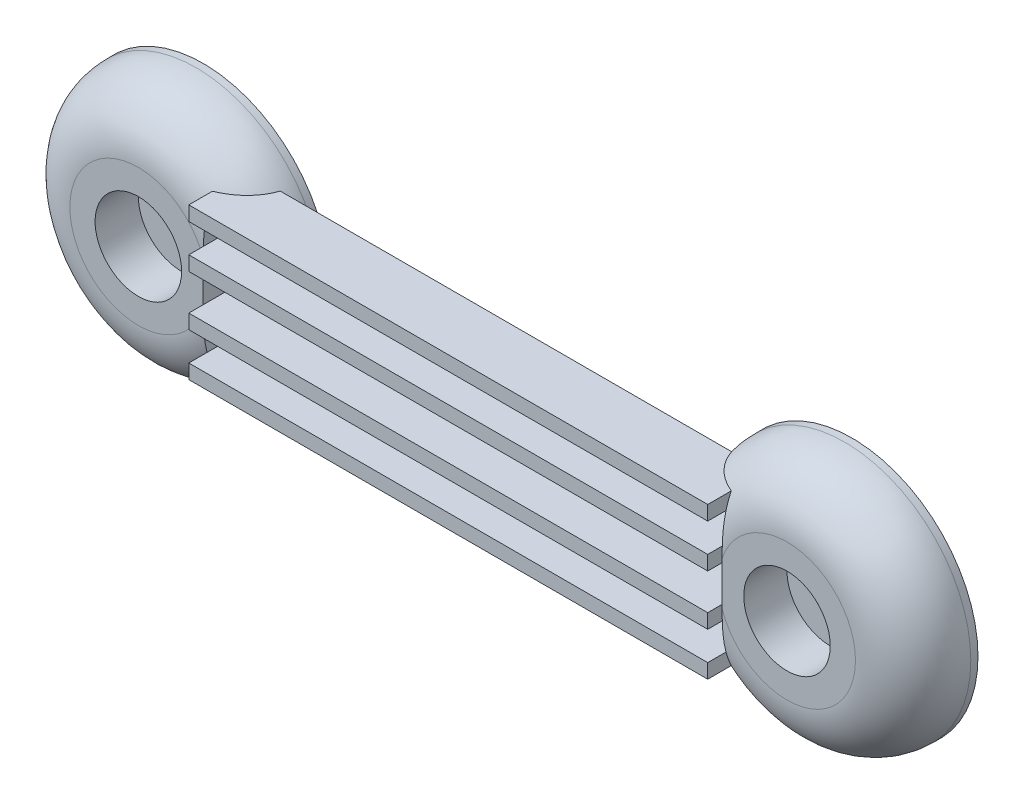
SolidWorks part; units mm, degrees
ref_plane "Alzado" through (0, 0, 0) normal (0, 0, 1) x (1, 0, 0)
ref_plane "Planta" through (0, 0, 0) normal (0, 1, 0) x (1, 0, 0)
ref_plane "Vista lateral" through (0, 0, 0) normal (1, 0, 0) x (0, 0, -1)
sketch "Croquis1" plane through (0, 0, 0) normal (0, 0, 1) x (1, 0, 0)
  line L0 (-45, 0) -> (45, 0) construction
  circle A0 centre (45, 0) radius 17.5
  circle A1 centre (-45, 0) radius 17.5
  dimension "D1" = 90
extrude "Saliente-Extruir1" add sketch "Croquis1" along normal blind 9
fillet "Redondeo1" radius 8 1 edges at (-27.5, 0, 9)
fillet "Redondeo2" radius 8 1 edges at (62.5, 0, 9)
ref_plane "Plano1" through (0, 0, 3) normal (0, 0, 1) x (1, 0, 0)
sketch "Croquis5" plane through (0, 0, 3) normal (0, 0, 1) x (1, 0, 0)
  line L0 (-36, -10.5) -> (36, -10.5)
  line L1 (-36, -10.5) -> (-36, 10.5)
  line L2 (36, -10.5) -> (36, 10.5)
  line L3 (-36, 10.5) -> (36, 10.5)
  line L4 (-36, -10.5) -> (36, 10.5) construction
  line L5 (36, -10.5) -> (-36, 10.5) construction
  circle A0 centre (45, 0) radius 9.5 construction
  point P1 (0, 0)
  dimension "D1" = 10.5
  dimension "D2" = 9
extrude "Saliente-Extruir2" add sketch "Croquis5" along normal blind 8
sketch "Croquis6" plane through (0, 0, 11) normal (0, 0, 1) x (1, 0, 0)
  line L4 (-36, 10.5) -> (-36, -10.5)
  line L5 (-36, -10.5) -> (36, -10.5)
  line L6 (36, -10.5) -> (36, 10.5)
  line L7 (36, 10.5) -> (-36, 10.5)
  line L8 (-36, 10.5) -> (-36, -10.5)
  line L9 (-36, -10.5) -> (36, -10.5)
  line L10 (36, -10.5) -> (36, 10.5)
  line L11 (36, 10.5) -> (-36, 10.5)
  line L12 (36, 8.5) -> (-36, 8.5)
  line L13 (-36, -8.5) -> (36, -8.5)
  line L14 (-36, -4.5) -> (36, -4.5)
  line L19 (36, 4.5) -> (-36, 4.5)
  line L20 (36, 2.5) -> (-36, 2.5)
  line L21 (-36, -2.5) -> (36, -2.5)
  line M5 (-36, 10.5) -> (-36, -10.5)
  dimension "D1" = 0
  dimension "D2" = 2
  dimension "D3" = 2
  dimension "D4" = 4
  dimension "D5" = 4
  dimension "D6" = 2
  dimension "D7" = 2
extrude "Cortar-Extruir1" cut sketch "Croquis6" against normal blind 7 contours L19 L10 L12 L8 | L8 L21 L10 L20 | L14 L13 L10 M5
sketch "Croquis8" plane through (0, 0, 9) normal (0, 0, 1) x (1, 0, 0)
  circle A0 centre (-45, 0) radius 6
  circle A1 centre (45, 0) radius 6
extrude "Cortar-Extruir2" cut sketch "Croquis8" against normal blind 6
sketch "Croquis9" plane through (0, 0, 3) normal (0, 0, 1) x (1, 0, 0)
  circle A0 centre (45, 0) radius 2.5
  circle A1 centre (-45, 0) radius 2.5
extrude "Cortar-Extruir3" cut sketch "Croquis9" against normal through all
sketch "Croquis10" plane through (0, 0, 0) normal (0, 0, -1) x (-1, 0, 0)
  line L0 (-27.5, 0) -> (-45, 0) construction
  line L1 (-45, 17.5) -> (-45, 0) construction
  circle A1 centre (-45, 0) radius 17.5 construction
